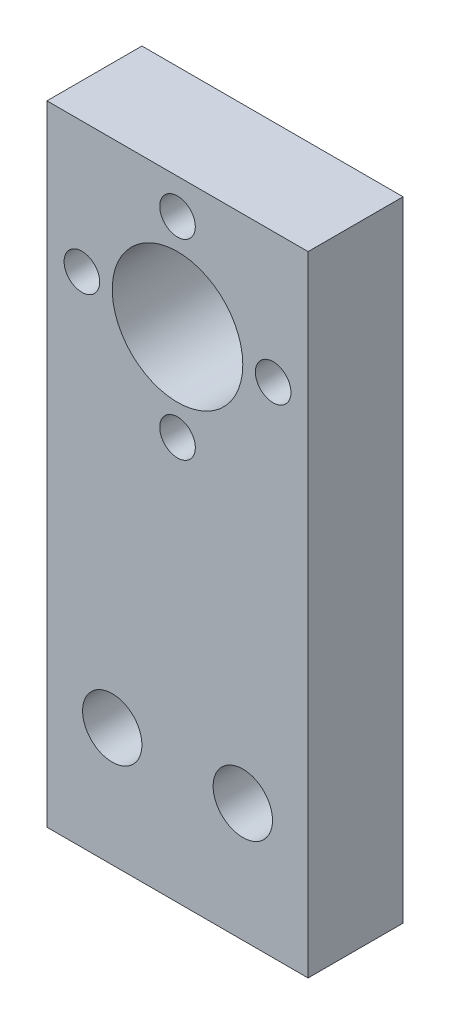
SolidWorks part; units mm, degrees
ref_plane "前视基准面" through (0, 0, 0) normal (0, 0, 1) x (1, 0, 0)
ref_plane "上视基准面" through (0, 0, 0) normal (0, 1, 0) x (1, 0, 0)
ref_plane "右视基准面" through (0, 0, 0) normal (1, 0, 0) x (0, 0, -1)
sketch "草图1" plane through (0, 0, 0) normal (0, 0, 1) x (1, 0, 0)
  line L0 (-18.0088, -9.1991) -> (3.9912, -9.1991) construction
  line L1 (-18.0088, 23.8009) -> (3.9912, 23.8009)
  line L2 (-18.0088, 23.8009) -> (-18.0088, -29.1991)
  line L3 (-18.0088, -29.1991) -> (3.9912, -29.1991)
  line L4 (3.9912, 23.8009) -> (3.9912, -29.1991)
  line L5 (-18.0088, 23.8009) -> (3.9912, -29.1991) construction
  line L6 (-18.0088, -29.1991) -> (3.9912, 23.8009) construction
  line L7 (3.9912, -9.1991) -> (-18.0088, -29.1991) construction
  line L8 (-7.0088, -9.1991) -> (-7.0088, -29.1991) construction
  line L9 (-7.0088, -29.1991) -> (-18.0088, -9.1991) construction
  line L10 (-18.0088, -9.1991) -> (-7.0088, -9.1991) construction
  line L11 (-7.0088, -9.1991) -> (-18.0088, -29.1991) construction
  line L12 (-7.0088, -9.1991) -> (3.9912, -29.1991) construction
  line L13 (3.9912, -9.1991) -> (-7.0088, -29.1991) construction
  line L14 (-7.0088, 23.8009) -> (-7.0088, 12.8009) construction
  circle A0 centre (-12.5088, -19.1991) radius 2.5
  circle A1 centre (-1.5088, -19.1991) radius 2.5
  circle A2 centre (-7.0088, 12.8009) radius 5.5
  circle A4 centre (-7.0088, 20.8589) radius 1.5
  circle A5 centre (1.0492, 12.8009) radius 1.5
  circle A6 centre (-7.0088, 4.7428) radius 1.5
  circle A7 centre (-15.0669, 12.8009) radius 1.5
  point P0 (-18.0088, -9.1991)
  dimension "D4" = 11
  dimension "D1" = 22
  dimension "D2" = 53
  dimension "D3" = 20
extrude "凸台-拉伸1" add sketch "草图1" along normal blind 8
